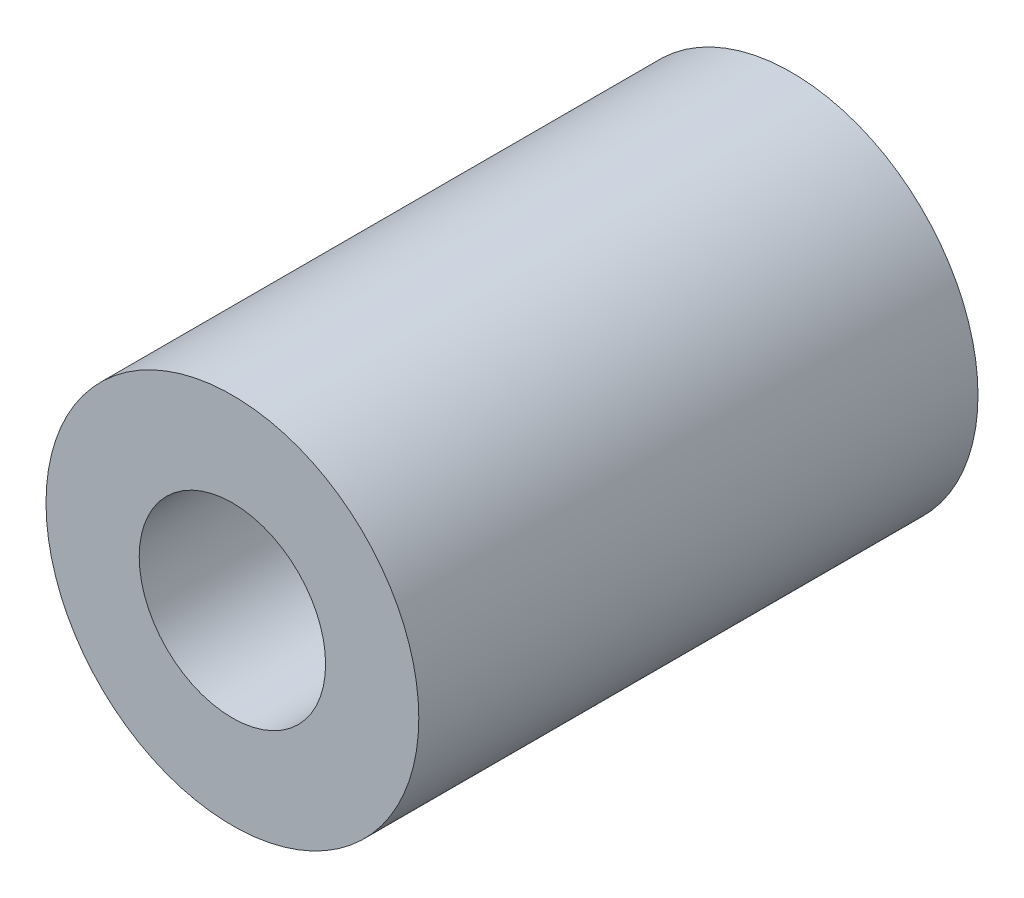
SolidWorks part; units mm, degrees
ref_plane "Front Plane" through (0, 0, 0) normal (0, 0, 1) x (1, 0, 0)
ref_plane "Top Plane" through (0, 0, 0) normal (0, 1, 0) x (1, 0, 0)
ref_plane "Right Plane" through (0, 0, 0) normal (1, 0, 0) x (0, 0, -1)
sketch "Sketch1" plane through (0, 0, 0) normal (0, 0, 1) x (1, 0, 0)
  circle A0 centre (0, 0) radius 10
  dimension "D1" = 20
extrude "Boss-Extrude1" add sketch "Sketch1" along normal blind 30 contours A0
sketch "Sketch2" plane through (0, 0, 0) normal (0, 0, -1) x (-1, 0, 0)
  circle A0 centre (0, 0) radius 5
  dimension "D1" = 10
extrude "Cut-Extrude1" cut sketch "Sketch2" against normal blind 50
